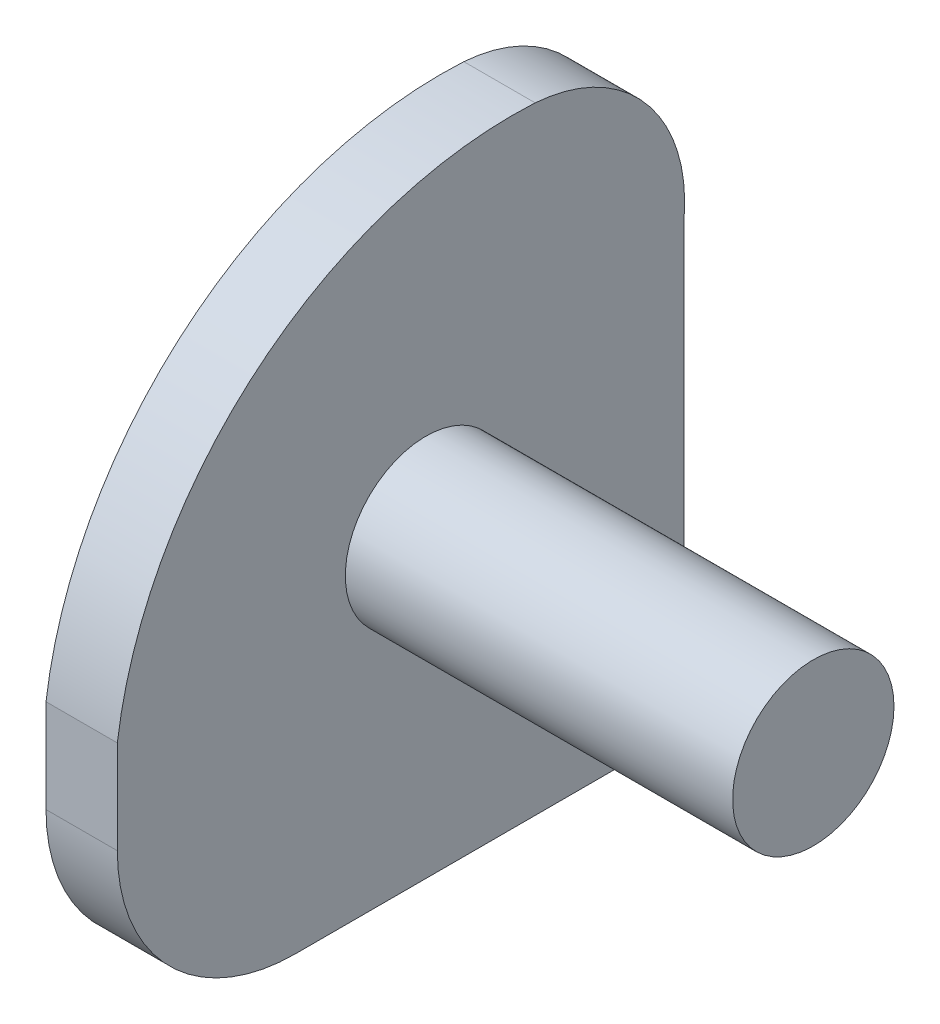
SolidWorks part; units mm, degrees
ref_plane "Front Plane" through (0, 0, 0) normal (0, 0, 1) x (1, 0, 0)
ref_plane "Top Plane" through (0, 0, 0) normal (0, 1, 0) x (1, 0, 0)
ref_plane "Right Plane" through (0, 0, 0) normal (1, 0, 0) x (0, 0, -1)
sketch "Sketch3" plane through (0, 0, 0) normal (1, 0, 0) x (0, 0, -1)
  line L2 (0, -60) -> (0, -86.1848)
  line L3 (50, -136.1848) -> (59.297, -136.1848)
  line L16 (158.939, -11.4803) -> (158.939, -50)
  line L17 (59.297, -136.1848) -> (138.939, -136.1848)
  line L18 (158.939, -50) -> (158.939, -116.1848)
  arc A1 (0, -86.1848) -> (50, -136.1848) centre (50, -86.1848) ccw
  arc A8 (0, -60) -> (117.1561, 36.8308) centre (110.8736, -74.8572) cw
  arc A13 (117.1561, 36.8308) -> (158.939, -11.4803) centre (113.892, -8.2162) cw
  arc A14 (138.939, -136.1848) -> (158.939, -116.1848) centre (138.939, -116.1848) ccw
  point P13 (0, 0)
  dimension "D1" = 20
  dimension "D2" = 50
extrude "Boss-Extrude1" add sketch "Sketch3" along normal blind 20 contours L3 L17 A14 L18 L16 A13 A8 L2 A1
scale "Scale1" scale about centroid uniform scaling yes scale factor 0.110511
sketch "Sketch4" plane through (11.1051, 0, 0) normal (1, 0, 0) x (0, 0, -1)
  line L0 (93.5013, -50.8771) -> (93.5013, -62.4481) construction
  circle A0 centre (85.5013, -55.2882) radius 2.5
  dimension "D1" = 5
  dimension "D3" = 8
  dimension "D2" = 9.75
extrude "Boss-Extrude2" add sketch "Sketch4" along normal blind 12
